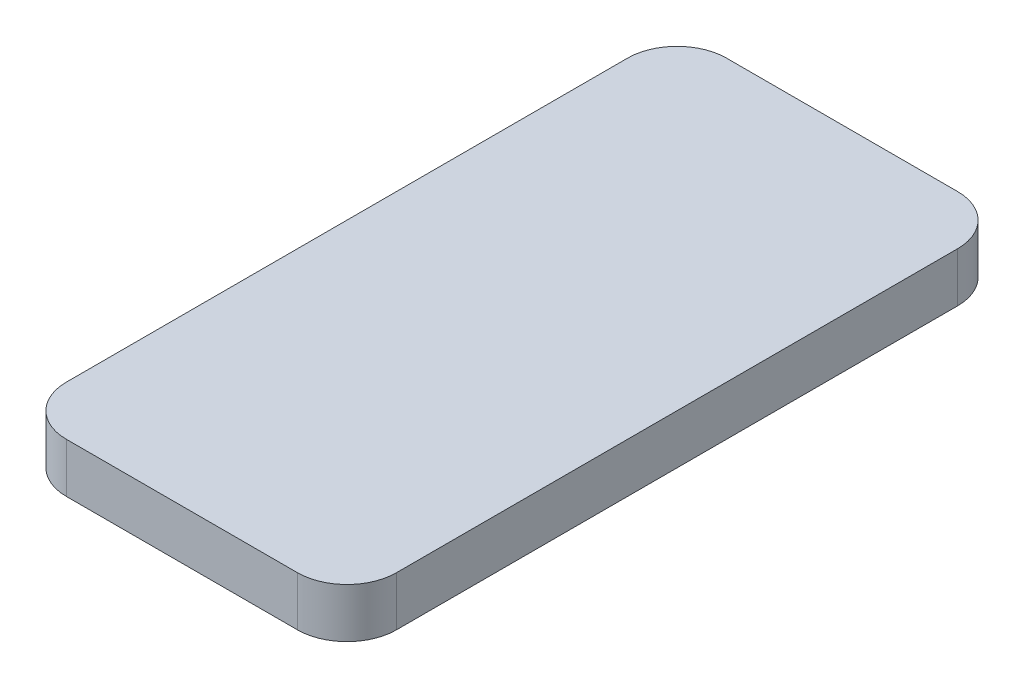
SolidWorks part; units mm, degrees
ref_plane "前视基准面" through (0, 0, 0) normal (0, 0, 1) x (1, 0, 0)
ref_plane "上视基准面" through (0, 0, 0) normal (0, 1, 0) x (1, 0, 0)
ref_plane "右视基准面" through (0, 0, 0) normal (1, 0, 0) x (0, 0, -1)
sketch "草图1" plane through (0, 0, 0) normal (0, 1, 0) x (1, 0, 0)
  line L1 (0, 0) -> (20, 0)
  line L2 (0, 0) -> (0, 40)
  line L3 (0, 40) -> (20, 40)
  line L4 (20, 0) -> (20, 40)
  dimension "D1" = 20
  dimension "D2" = 40
extrude "凸台-拉伸1" add sketch "草图1" along normal blind 3
fillet "圆角1" radius 3 4 edges at (20, 1.5, -40) (0, 1.5, -40) (0, 1.5, 0) (20, 1.5, 0)
